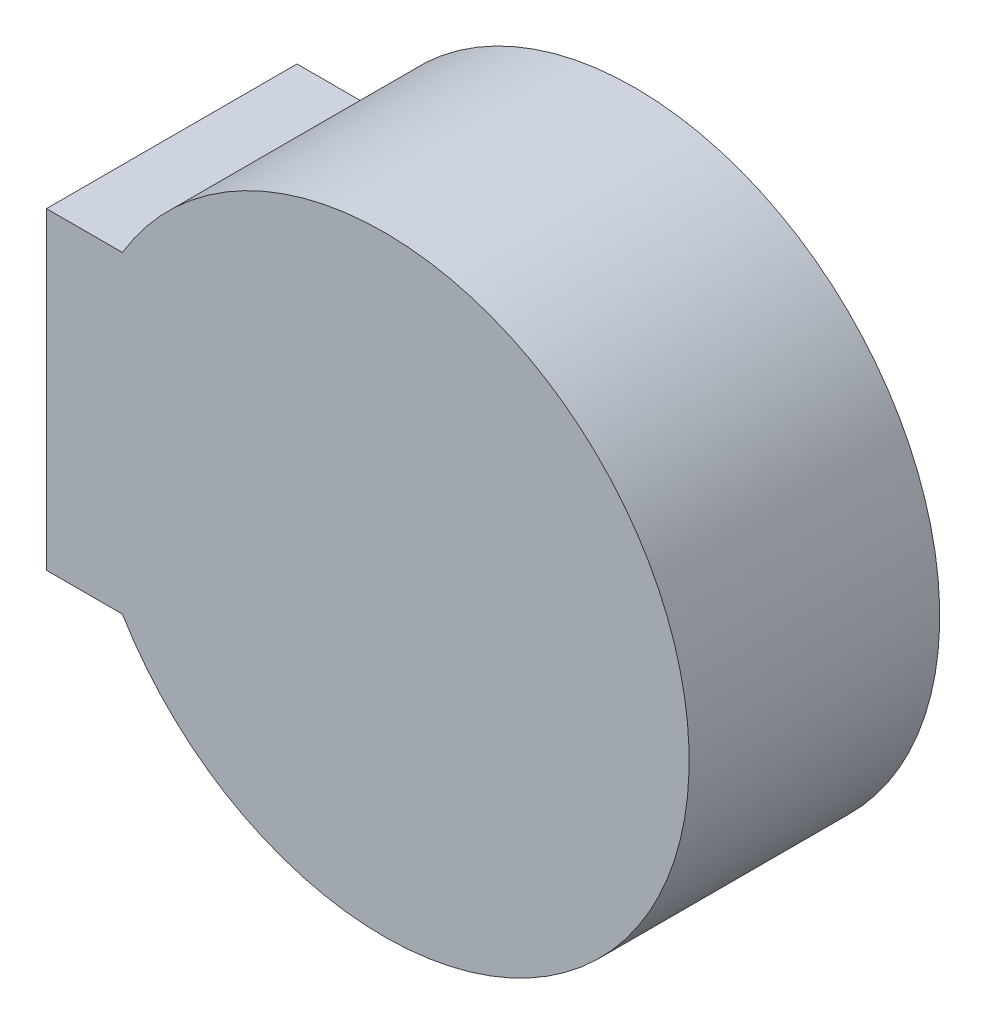
SolidWorks part; units mm, degrees
ref_plane "Front Plane" through (0, 0, 0) normal (0, 0, 1) x (1, 0, 0)
ref_plane "Top Plane" through (0, 0, 0) normal (0, 1, 0) x (1, 0, 0)
ref_plane "Right Plane" through (0, 0, 0) normal (1, 0, 0) x (0, 0, -1)
sketch "Sketch1" plane through (0, 0, 0) normal (0, 0, 1) x (1, 0, 0)
  circle A0 centre (0, 0) radius 14.224
  dimension "D1" = 28.448
extrude "Boss-Extrude1" add sketch "Sketch1" along normal blind 11.684
sketch "Sketch2" plane through (0, 0, 11.684) normal (0, 0, 1) x (1, 0, 0)
  line L0 (-15.748, 0) -> (0, 0) construction
  line L2 (-15.748, 7.3025) -> (-4.8856, 7.3025)
  line L3 (-15.748, 7.3025) -> (-15.748, -7.3025)
  line L4 (-15.748, -7.3025) -> (-4.8856, -7.3025)
  line L5 (-4.8856, 7.3025) -> (-4.8856, -7.3025)
  circle A0 centre (0, 0) radius 14.224 construction
  dimension "D1" = 15.748
  dimension "D2" = 14.605
extrude "Boss-Extrude2" add sketch "Sketch2" against normal up to surface (11.684 mm away) up to face at (14.224, 0, 0)
